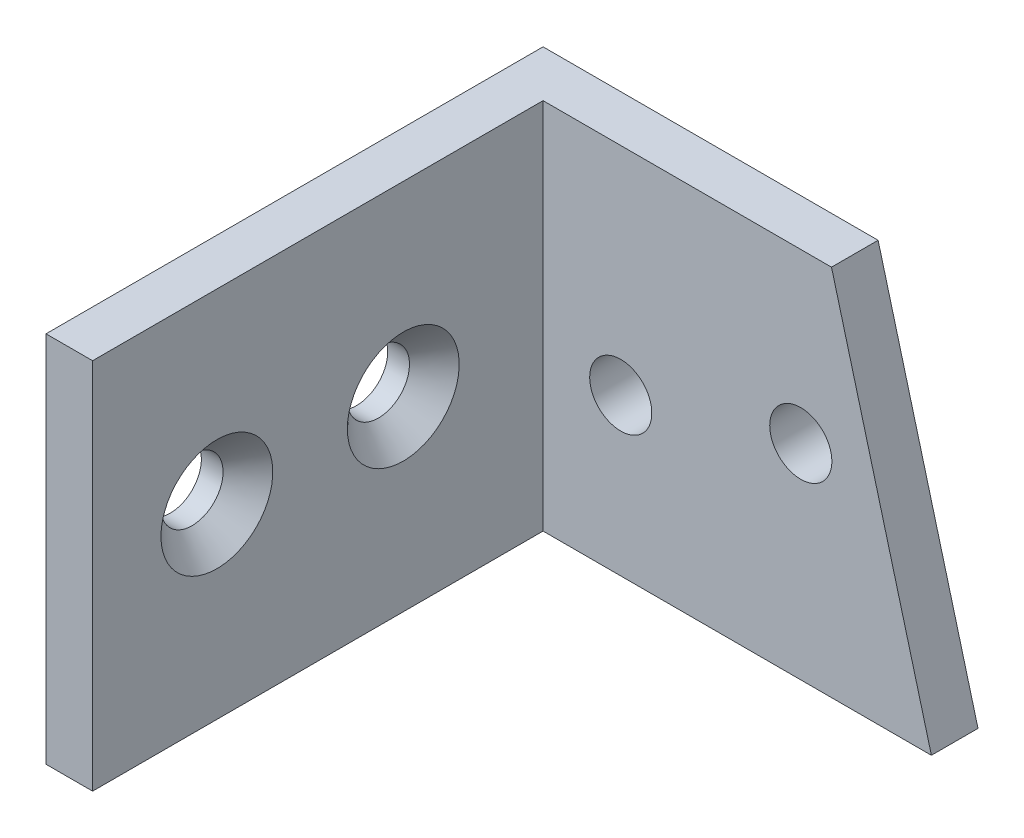
SolidWorks part; units mm, degrees
material "6061 Alloy"
ref_plane "Front Plane" through (0, 0, 0) normal (0, 0, 1) x (1, 0, 0)
ref_plane "Top Plane" through (0, 0, 0) normal (0, 1, 0) x (1, 0, 0)
ref_plane "Right Plane" through (0, 0, 0) normal (1, 0, 0) x (0, 0, -1)
sketch "Sketch1" plane through (0, 0, 0) normal (0, 1, 0) x (1, 0, 0)
  line L0 (0, 0) -> (0, 46.0375)
  line L1 (0, 46.0375) -> (39.6875, 46.0375)
  line L2 (39.6875, 46.0375) -> (39.6875, 50.8)
  line L3 (39.6875, 50.8) -> (-4.7625, 50.8)
  line L4 (-4.7625, 50.8) -> (-4.7625, 0)
  line L5 (-4.7625, 0) -> (0, 0)
  dimension "D1" = 44.45
  dimension "D2" = 50.8
  dimension "D3" = 4.7625
  dimension "D4" = 4.7625
extrude "Boss-Extrude1" add sketch "Sketch1" along normal blind 38.1
sketch "Sketch2" plane through (0, 0, -50.8) normal (0, 0, -1) x (-1, 0, 0)
  line L2 (-39.6875, 24.5038) -> (4.7625, 12.5935) construction
  line L3 (-39.6875, 38.1) -> (-39.6875, 0) construction
  line L4 (4.7625, 38.1) -> (4.7625, 0) construction
  line L5 (-39.6875, 38.1) -> (4.7625, 38.1) construction
  circle A0 centre (-26.3384, 20.9269) radius 3.175
  circle A1 centre (-7.9375, 15.9964) radius 3.175
  dimension "D1" = 6.35
  dimension "D2" = 15
  dimension "D3" = 0
  dimension "D4" = 19.05
  dimension "D7" = 6.35
  dimension "D6" = 12.7
  dimension "D5" = 0
extrude "Cut-Extrude1" cut sketch "Sketch2" against normal blind 38.1
sketch "Sketch3" plane through (-4.7625, 0, 0) normal (-1, 0, 0) x (0, 0, 1)
  line L2 (-50.8, 0) -> (0, 0) construction
  line L3 (0, 38.1) -> (0, 0) construction
  circle A0 centre (-12.7, 19.05) radius 3.175
  circle A1 centre (-31.75, 19.05) radius 3.175
  dimension "D1" = 6.35
  dimension "D2" = 6.35
  dimension "D3" = 19.05
  dimension "D4" = 19.05
  dimension "D5" = 12.7
  dimension "D6" = 19.05
extrude "Cut-Extrude3" cut sketch "Sketch3" against normal up to next
sketch "Sketch4" plane through (0, 0, -50.8) normal (0, 0, -1) x (-1, 0, 0)
  line L0 (-29.4786, 38.1) -> (-39.6875, 0)
  line L3 (-39.6875, 38.1) -> (4.7625, 38.1) construction
  line L4 (-39.6875, 38.1) -> (-39.6875, 0) construction
  dimension "D1" = 15
  dimension "D2" = 0
extrude "Cut-Extrude4" cut sketch "Sketch4" against normal through all and the other way through all flip side to cut contours L0
chamfer "Chamfer1" distance 2.54 angle 45 2 edges at (0, 19.05, -9.525) (0, 19.05, -28.575)
